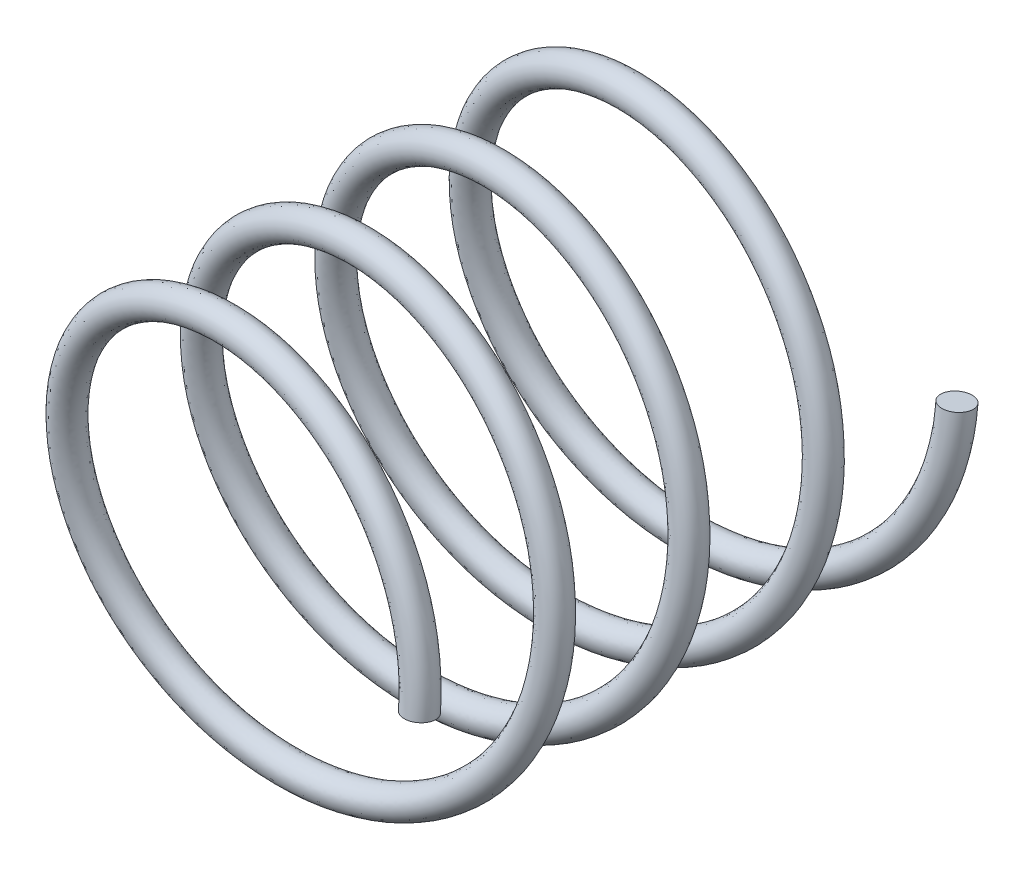
SolidWorks part; units mm, degrees
material "AISI 1020"
ref_plane "Front" through (0, 0, 0) normal (0, 0, 1) x (1, 0, 0)
ref_plane "Top" through (0, 0, 0) normal (0, 1, 0) x (1, 0, 0)
ref_plane "Right" through (0, 0, 0) normal (1, 0, 0) x (0, 0, -1)
sketch "Sketch1" plane through (0, 0, 0) normal (0, 0, 1) x (1, 0, 0)
  circle A0 centre (0, 0) radius 7
curve "Helix/Spiral1" pitch 4.5 height 18 turns 4
sweep "Sweep1" add path "Helix/Spiral1" circular profile diameter 1 parameters "D3"=1
